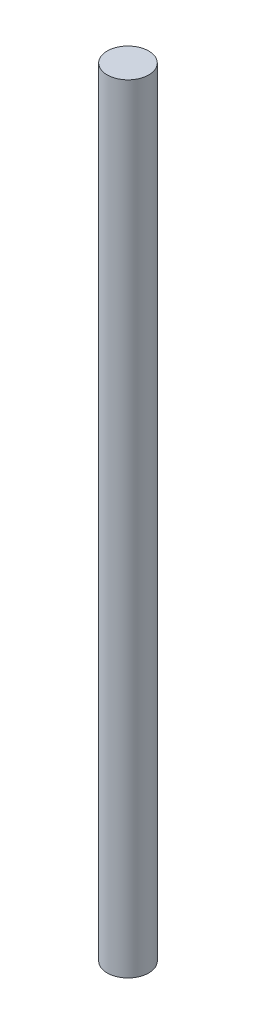
SolidWorks part; units mm, degrees
ref_plane "Alzado" through (0, 0, 0) normal (0, 0, 1) x (1, 0, 0)
ref_plane "Planta" through (0, 0, 0) normal (0, 1, 0) x (1, 0, 0)
ref_plane "Vista lateral" through (0, 0, 0) normal (1, 0, 0) x (0, 0, -1)
sketch "Croquis1" plane through (0, 0, 0) normal (0, 1, 0) x (1, 0, 0)
  circle A0 centre (0, 0) radius 4
  dimension "D1" = 8
extrude "Saliente-Extruir1" add sketch "Croquis1" along normal mid plane 150
